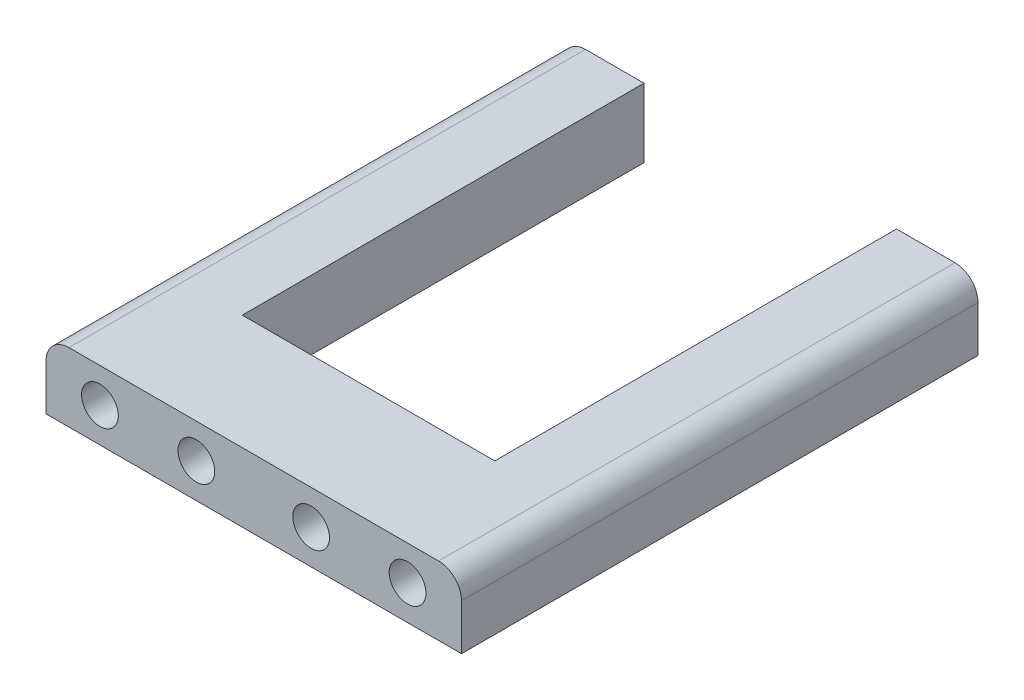
SolidWorks part; units mm, degrees
material "Thornel VCB-20 Carbon Cloth"
ref_plane "Front Plane" through (0, 0, 0) normal (0, 0, 1) x (1, 0, 0)
ref_plane "Top Plane" through (0, 0, 0) normal (0, 1, 0) x (1, 0, 0)
ref_plane "Right Plane" through (0, 0, 0) normal (1, 0, 0) x (0, 0, -1)
sketch "Sketch1" plane through (0, 0, 0) normal (0, 1, 0) x (1, 0, 0)
  line L1 (-18.1, -22.5) -> (18.1, -22.5)
  line L2 (-18.1, -22.5) -> (-18.1, 22.5)
  line L3 (-18.1, 22.5) -> (18.1, 22.5)
  line L4 (18.1, -22.5) -> (18.1, 22.5)
  line L5 (-18.1, -22.5) -> (18.1, 22.5) construction
  line L6 (-18.1, 22.5) -> (18.1, -22.5) construction
  point P0 (0, 0)
  dimension "D1" = 36.2
  dimension "D2" = 45
extrude "Boss-Extrude1" add sketch "Sketch1" along normal blind 6
sketch "Sketch2" plane through (0, 0, 22.5) normal (0, 0, 1) x (1, 0, 0)
  line L0 (0, 6) -> (0, 0) construction
  line L1 (-18.1, 6) -> (18.1, 6) construction
  circle A0 centre (-5, 3) radius 1.6
  circle A1 centre (-13.4, 3) radius 1.6
  circle A2 centre (5, 3) radius 1.6
  circle A3 centre (13.4, 3) radius 1.6
  dimension "D1" = 3.2
  dimension "D2" = 3.2
  dimension "D3" = 5
  dimension "D4" = 13.4
extrude "Cut-Extrude1" cut sketch "Sketch2" against normal through all
sketch "Sketch4" plane through (0, 0, -22.5) normal (0, 0, -1) x (-1, 0, 0)
  line L0 (0, 0) -> (0, 6) construction
  line L1 (-18.1, 0) -> (18.1, 0) construction
  line L2 (-18.1, 6) -> (18.1, 6) construction
  line L4 (-11, 0) -> (11, 0)
  line L5 (-11, 0) -> (-11, 6)
  line L6 (-11, 6) -> (11, 6)
  line L7 (11, 0) -> (11, 6)
  line L8 (-11, 0) -> (11, 6) construction
  line L9 (-11, 6) -> (11, 0) construction
  point P6 (0, 3)
  dimension "D1" = 22
extrude "Cut-Extrude2" cut sketch "Sketch4" against normal blind 35
fillet "Fillet1" radius 2 2 edges at (-18.1, 6, 0) (18.1, 6, 0)
